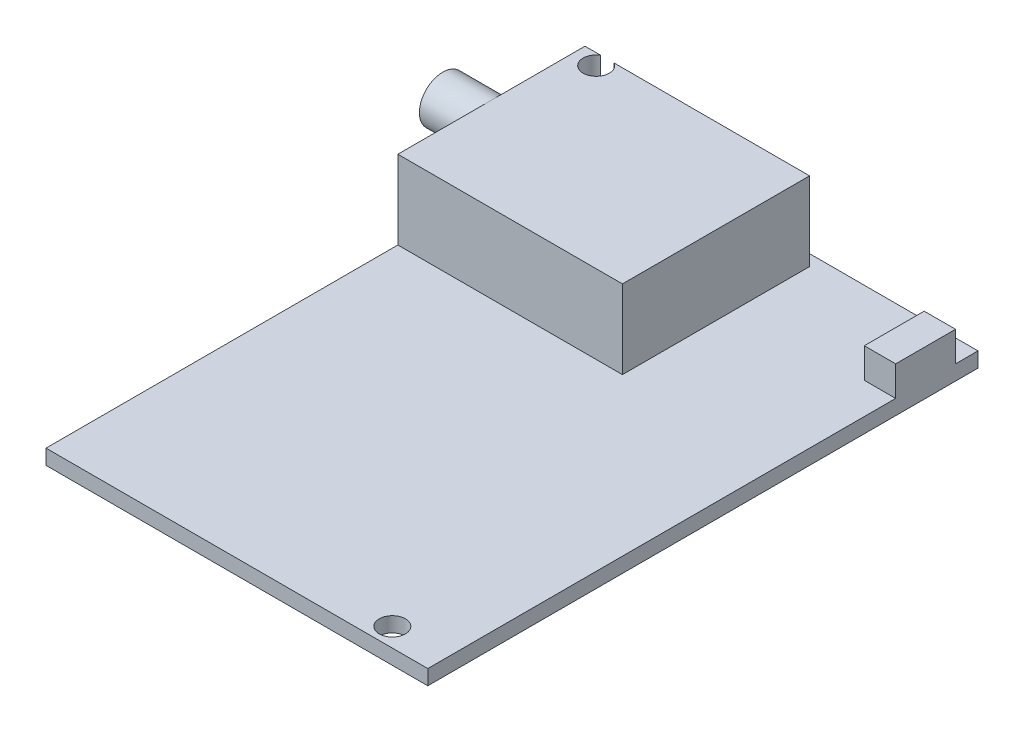
SolidWorks part; units mm, degrees
ref_plane "Front Plane" through (0, 0, 0) normal (0, 0, 1) x (1, 0, 0)
ref_plane "Top Plane" through (0, 0, 0) normal (0, 1, 0) x (1, 0, 0)
ref_plane "Right Plane" through (0, 0, 0) normal (1, 0, 0) x (0, 0, -1)
sketch "Sketch1" plane through (0, 0, 0) normal (0, 1, 0) x (1, 0, 0)
  line L1 (-13.0645, 20.1768) -> (0, 20.1768)
  line L2 (-13.0645, 20.1768) -> (-13.0645, 0)
  line L3 (-13.0645, 0) -> (0, 0)
  line L4 (0, 20.1768) -> (0, 0)
extrude "Boss-Extrude1" add sketch "Sketch1" along normal blind 5
sketch "Sketch2" plane through (0, 5, 0) normal (0, 1, 0) x (1, 0, 0)
  line L0 (0, 20.1768) -> (-13.0645, 20.1768) construction
  line L1 (-32.0322, 56.9268) -> (18.9678, 56.9268)
  line L2 (-32.0322, 56.9268) -> (-32.0322, -16.5732)
  line L3 (-32.0322, -16.5732) -> (18.9678, -16.5732)
  line L4 (18.9678, 56.9268) -> (18.9678, -16.5732)
  line L5 (-32.0322, 56.9268) -> (18.9678, -16.5732) construction
  line L6 (-32.0322, -16.5732) -> (18.9678, 56.9268) construction
  point P0 (-6.5322, 20.1768)
  dimension "D1" = 51
  dimension "D2" = 73.5
extrude "Boss-Extrude2" add sketch "Sketch2" along normal blind 2
sketch "Sketch3" plane through (0, 7, 0) normal (0, 1, 0) x (1, 0, 0)
  line L1 (-32.0322, 55.4268) -> (-2.0322, 55.4268)
  line L2 (-32.0322, 55.4268) -> (-32.0322, 30.4268)
  line L3 (-32.0322, 30.4268) -> (-2.0322, 30.4268)
  line L4 (-2.0322, 55.4268) -> (-2.0322, 30.4268)
  line L5 (-32.0322, 55.4268) -> (-2.0322, 30.4268) construction
  line L6 (-32.0322, 30.4268) -> (-2.0322, 55.4268) construction
  line L7 (18.9678, 56.9268) -> (-32.0322, 56.9268) construction
  line L8 (-32.0322, 56.9268) -> (-32.0322, -16.5732) construction
  point P0 (-17.0322, 42.9268)
  dimension "D1" = 25
  dimension "D2" = 30
  dimension "D3" = 0
  dimension "D4" = 1.5
extrude "Boss-Extrude3" add sketch "Sketch3" along normal blind 10.5 contours L2 L3 L4 L1
sketch "Sketch7" plane through (-32.0322, 0, 0) normal (-1, 0, 0) x (0, 0, 1)
  line L0 (-55.4268, 17.5) -> (-30.4268, 17.5) construction
  line L1 (-55.4268, 17.5) -> (-55.4268, 7) construction
  circle A0 centre (-42.9268, 14.375) radius 3.125
  dimension "D1" = 6.25
  dimension "D2" = 3.125
  dimension "D3" = 12.5
extrude "Boss-Extrude5" add sketch "Sketch7" along normal blind 6.5
sketch "Sketch8" plane through (0, 7, 0) normal (0, 1, 0) x (1, 0, 0)
  line L0 (18.9678, -16.5732) -> (18.9678, 56.9268) construction
  line L1 (18.9678, 53.9268) -> (14.7785, 53.9268)
  line L2 (18.9678, 53.9268) -> (18.9678, 45.9268)
  line L3 (18.9678, 45.9268) -> (14.7785, 45.9268)
  line L4 (14.7785, 53.9268) -> (14.7785, 45.9268)
  line L5 (18.9678, 53.9268) -> (14.7785, 45.9268) construction
  line L6 (18.9678, 45.9268) -> (14.7785, 53.9268) construction
  line L7 (18.9678, 56.9268) -> (-32.0322, 56.9268) construction
  point P0 (16.8731, 49.9268)
  dimension "D1" = 8
  dimension "D2" = 0
  dimension "D3" = 3
extrude "Boss-Extrude6" add sketch "Sketch8" along normal blind 4
sketch "Sketch9" plane through (0, 7, 0) normal (0, 1, 0) x (1, 0, 0)
  line L0 (-32.0322, 56.9268) -> (-32.0322, 55.4268) construction
  line L1 (18.9678, 56.9268) -> (-32.0322, 56.9268) construction
  line L2 (18.9678, -16.5732) -> (18.9678, 45.9268) construction
  line L3 (-32.0322, -16.5732) -> (18.9678, -16.5732) construction
  circle A0 centre (11.7178, -14.0632) radius 1.75
  circle A1 centre (-29.0322, 53.9268) radius 1.75
  dimension "D1" = 3.5
  dimension "D2" = 3.5
  dimension "D3" = 3
  dimension "D4" = 3
  dimension "D5" = 7.25
  dimension "D6" = 2.51
extrude "Cut-Extrude1" cut sketch "Sketch9" against normal through all and the other way through all
